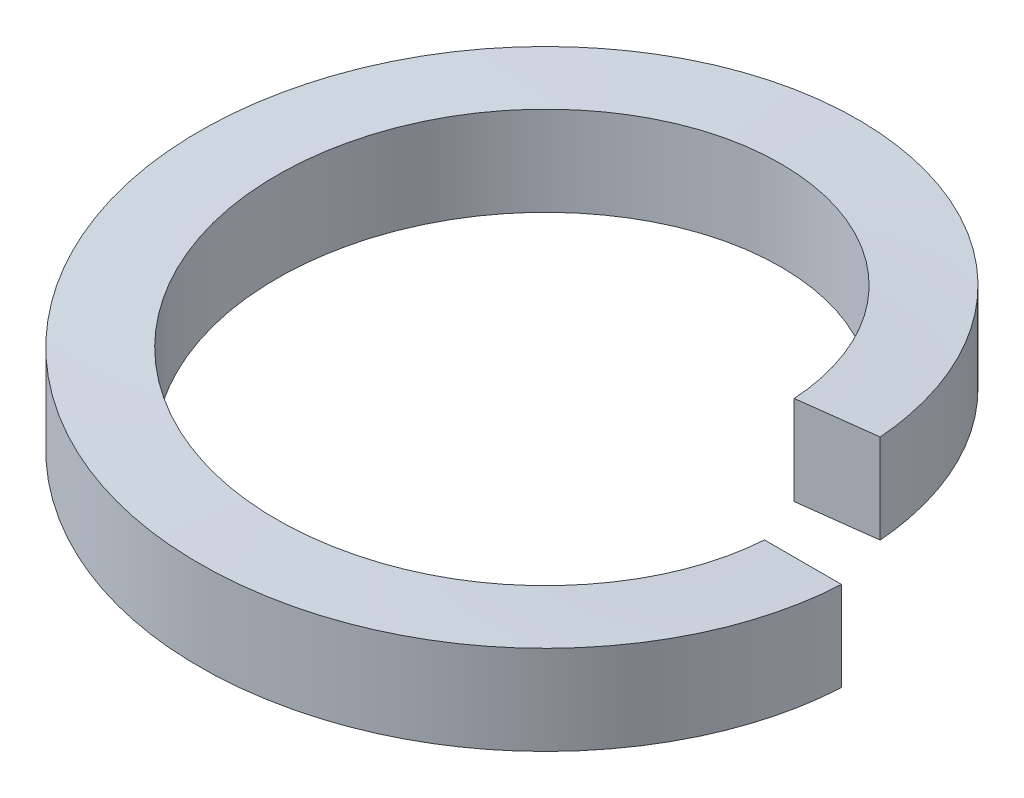
SolidWorks part; units mm, degrees
material "Brass"
ref_plane "Front Plane" through (0, 0, 0) normal (0, 0, 1) x (1, 0, 0)
ref_plane "Top Plane" through (0, 0, 0) normal (0, 1, 0) x (1, 0, 0)
ref_plane "Right Plane" through (0, 0, 0) normal (1, 0, 0) x (0, 0, -1)
sketch "Sketch1" plane through (0, 0, 0) normal (0, 0, 1) x (1, 0, 0)
  line L0 (0, 0) -> (0, 1.16) construction
  line L1 (3.28, 1.16) -> (4.28, 1.16)
  line L2 (3.28, 1.16) -> (3.28, 0)
  line L3 (3.28, 0) -> (4.28, 0)
  line L4 (4.28, 1.16) -> (4.28, 0)
  line L5 (3.28, 1.16) -> (4.28, 0) construction
  line L6 (3.28, 0) -> (4.28, 1.16) construction
  point P0 (3.78, 0.58)
  dimension "D1" = 1.16
  dimension "D2" = 1
  dimension "D3" = 6.56
sketch "Sketch2" plane through (0, 0, 0) normal (0, 1, 0) x (1, 0, 0)
  circle A0 centre (0, 0) radius 3.28
curve "Helix/Spiral1" pitch 1.4 height 1.372 turns 0.98
sweep "Sweep1" add profiles "Sketch1" path "Helix/Spiral1"
equation "\"panjang\"= 120"
equation "\"lebar\"=40"
equation "\"tinggi\"=10"
